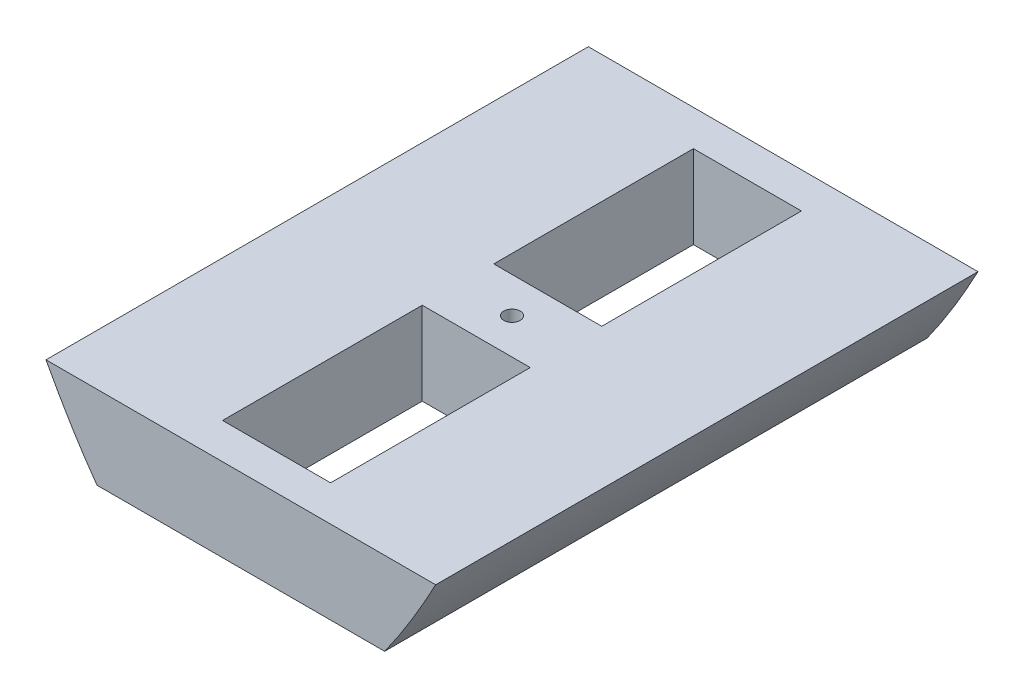
SolidWorks part; units mm, degrees
ref_plane "Front Plane" through (0, 0, 0) normal (0, 0, 1) x (1, 0, 0)
ref_plane "Top Plane" through (0, 0, 0) normal (0, 1, 0) x (1, 0, 0)
ref_plane "Right Plane" through (0, 0, 0) normal (1, 0, 0) x (0, 0, -1)
sketch "Sketch2" plane through (0, 0, 0) normal (0, 0, 1) x (1, 0, 0)
  line L0 (-127, 127) -> (127, 127)
  spline S0 degree 2 poles (-143.0272, 161.0769) (0, -161.0769) (143.0272, 161.0769) knots 0 0 0 1 1 1 construction
  spline S1 degree 2 poles (-127, 127) (0, -127) (127, 127) knots 0.056028 0.056028 0.056028 0.943972 0.943972 0.943972
extrude "Boss-Extrude2" add sketch "Sketch2" along normal blind 331.382
sketch "Sketch3" plane through (0, 127, 0) normal (0, 1, 0) x (1, 0, 0)
  line L0 (0, -309.5365) -> (0, 0) construction
  line L1 (-33, -21.8455) -> (33, -21.8455)
  line L2 (-33, -21.8455) -> (-33, -143.8455)
  line L3 (-33, -143.8455) -> (33, -143.8455)
  line L4 (33, -21.8455) -> (33, -143.8455)
  line L5 (-33, -187.5365) -> (33, -187.5365)
  line L6 (-33, -187.5365) -> (-33, -309.5365)
  line L7 (-33, -309.5365) -> (33, -309.5365)
  line L8 (33, -187.5365) -> (33, -309.5365)
  line L9 (-127, -165.691) -> (127, -165.691) construction
  line L10 (-127, -331.382) -> (-127, 0) construction
  line L11 (127, -331.382) -> (127, 0) construction
  line L12 (-33, -143.8455) -> (-33, -165.691) construction
  line L13 (33, -187.5365) -> (33, -165.691) construction
  line L14 (-33, -21.8455) -> (-33, 0) construction
  line L15 (127, 0) -> (-127, 0) construction
  circle A0 centre (0, -165.691) radius 5
  dimension "D3" = 10
  dimension "D1" = 122
  dimension "D2" = 66
extrude "Cut-Extrude2" cut sketch "Sketch3" against normal through all
sketch "Sketch4" plane through (0, 0, 0) normal (0, 0, -1) x (-1, 0, 0)
  line L1 (-90, 60.8) -> (90, 60.8)
  line L2 (-90, 60.8) -> (-90, 0)
  line L3 (-90, 0) -> (90, 0)
  line L4 (90, 60.8) -> (90, 0)
  dimension "D1" = 60.8
  dimension "D2" = 180
extrude "Cut-Extrude3" cut sketch "Sketch4" against normal through all
sketch "Sketch5" plane through (0, 0, 331.382) normal (0, 0, 1) x (1, 0, 0)
  line L0 (0, 0) -> (0, 111.6) construction
  line L1 (-130, 131.6) -> (130, 131.6)
  line L2 (-130, 131.6) -> (-130, 111.6)
  line L3 (-130, 111.6) -> (130, 111.6)
  line L4 (130, 131.6) -> (130, 111.6)
  dimension "D1" = 111.6
  dimension "D2" = 260
  dimension "D3" = 20
extrude "Cut-Extrude4" cut sketch "Sketch5" against normal through all
